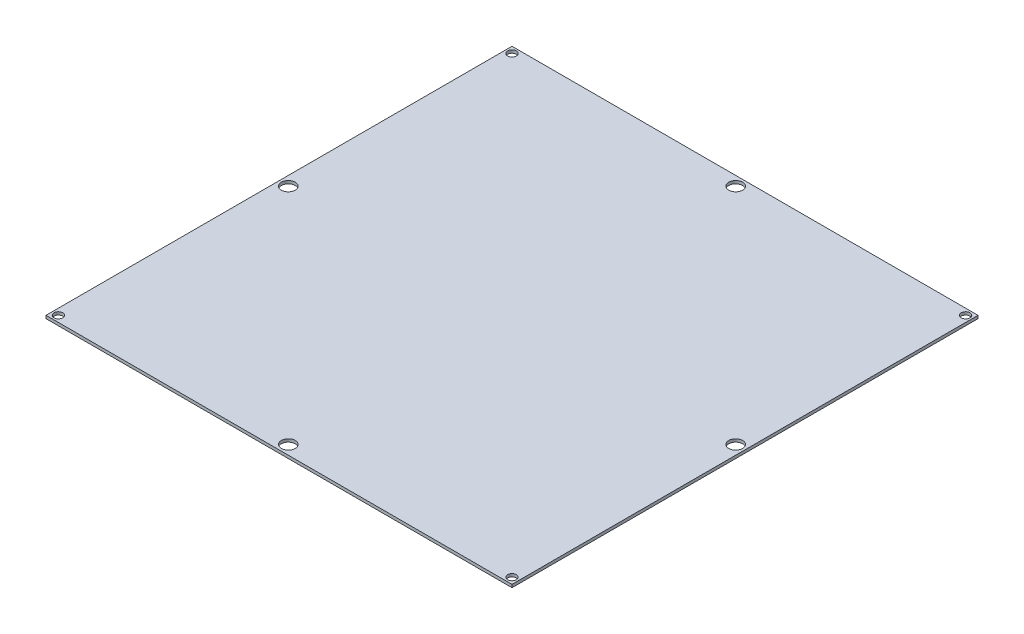
SolidWorks part; units mm, degrees
ref_plane "Front Plane" through (0, 0, 0) normal (0, 0, 1) x (1, 0, 0)
ref_plane "Top Plane" through (0, 0, 0) normal (0, 1, 0) x (1, 0, 0)
ref_plane "Right Plane" through (0, 0, 0) normal (1, 0, 0) x (0, 0, -1)
sketch "Sketch1" plane through (0, 0, 0) normal (0, 1, 0) x (1, 0, 0)
  line L0 (2.54, 187.96) -> (2.54, 190.5) construction
  line L1 (0, 0) -> (190.5, 0)
  line L2 (0, 0) -> (0, 190.5)
  line L3 (0, 190.5) -> (190.5, 190.5)
  line L4 (190.5, 0) -> (190.5, 190.5)
  line L5 (2.54, 187.96) -> (0, 187.96) construction
  line L6 (187.96, 2.54) -> (190.5, 2.54) construction
  line L7 (187.96, 2.54) -> (187.96, 0) construction
  line L8 (95.25, 190.5) -> (95.25, 0) construction
  line L9 (0, 95.25) -> (190.5, 95.25) construction
  circle A0 centre (2.54, 187.96) radius 1.796
  circle A1 centre (187.96, 187.96) radius 1.796
  circle A2 centre (187.96, 2.54) radius 1.796
  circle A3 centre (2.54, 2.54) radius 1.796
  circle A4 centre (95.25, 186.69) radius 2.84
  circle A5 centre (3.81, 95.25) radius 2.84
  circle A6 centre (95.25, 3.81) radius 2.84
  circle A7 centre (186.69, 95.25) radius 2.84
  point P25 (12.8901, 95.25)
  point P26 (95.25, 183.1762)
  point P27 (0, 0)
  dimension "D1" = 3.592
  dimension "D5" = 5.68
  dimension "D2" = 2.54
  dimension "D3" = 190.5
  dimension "D4" = 3.81
  dimension "D6" = 3.81
extrude "Boss-Extrude1" add sketch "Sketch1" along normal blind 1.2
